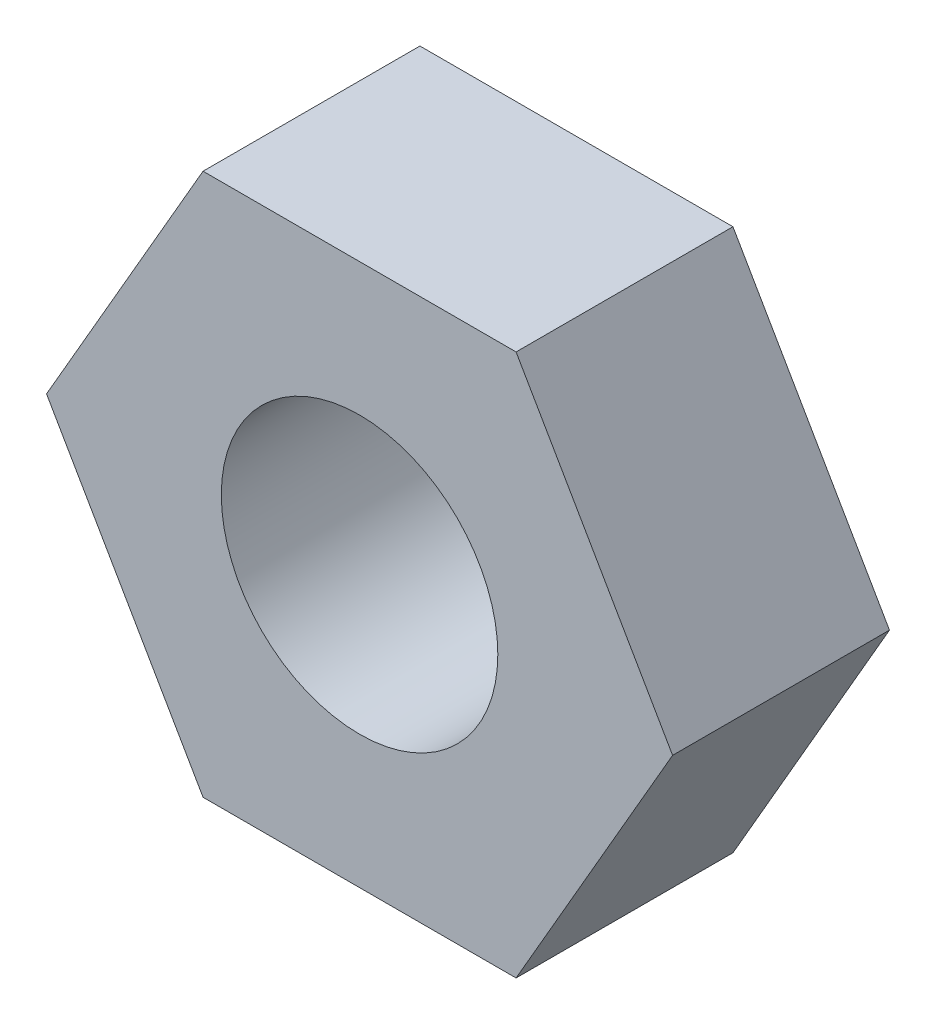
SolidWorks part; units mm, degrees
ref_plane "前视基准面" through (0, 0, 0) normal (0, 0, 1) x (1, 0, 0)
ref_plane "上视基准面" through (0, 0, 0) normal (0, 1, 0) x (1, 0, 0)
ref_plane "右视基准面" through (0, 0, 0) normal (1, 0, 0) x (0, 0, -1)
other "Configuration Table"
sketch "Sketch_Hex_blank" plane through (0, 0, 0) normal (0, 0, 1) x (1, 0, 0)
  line L0 (2.3094, 0) -> (1.1547, 2)
  line L1 (1.1547, 2) -> (-1.1547, 2)
  line L2 (-1.1547, 2) -> (-2.3094, 0)
  line L3 (-2.3094, 0) -> (-1.1547, -2)
  line L4 (-1.1547, -2) -> (1.1547, -2)
  line L5 (1.1547, -2) -> (2.3094, 0)
extrude "Hex_blank" add sketch "Sketch_Hex_blank" along normal blind 1.6 from offset 0
sketch "Sketch_Nominal_thread_envelope" plane through (0, 0, 0) normal (0, 0, 1) x (1, 0, 0)
  circle A0 centre (0, 0) radius 1.02
  dimension "D1" = 2.04
extrude "Nominal_thread_envelope" cut sketch "Sketch_Nominal_thread_envelope" along normal blind 3.6 from offset 1
